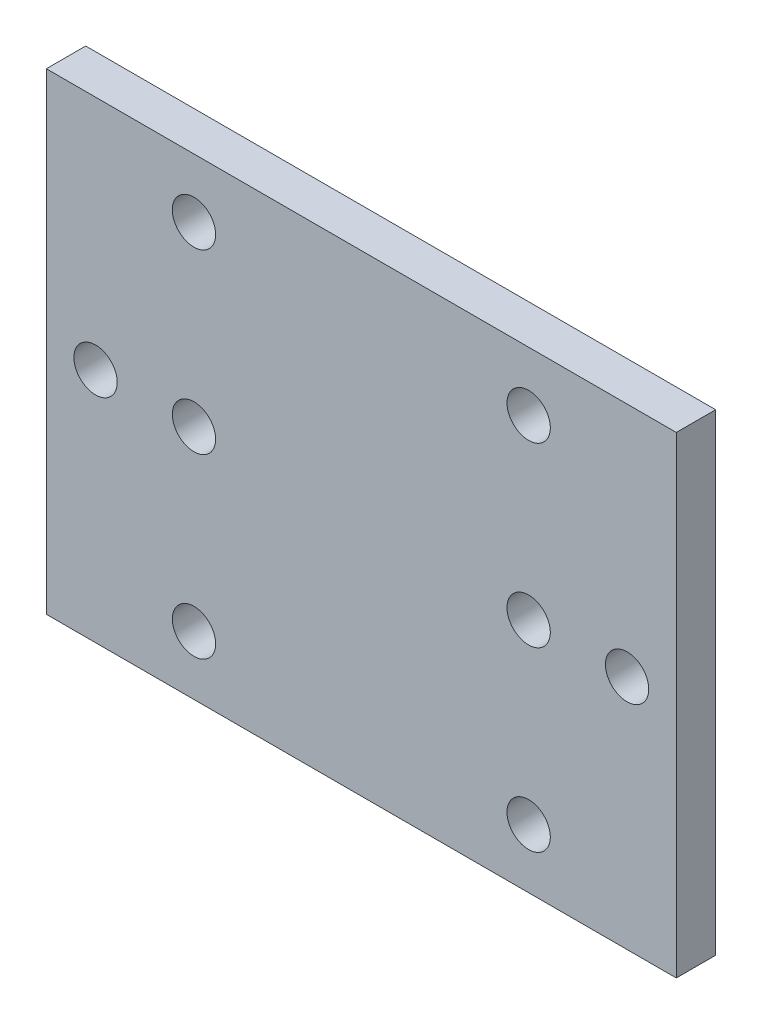
SolidWorks part; units mm, degrees
material "AISI 1015 Steel, Cold Drawn (SS)"
ref_plane "Front Plane" through (0, 0, 0) normal (0, 0, 1) x (1, 0, 0)
ref_plane "Top Plane" through (0, 0, 0) normal (0, 1, 0) x (1, 0, 0)
ref_plane "Right Plane" through (0, 0, 0) normal (1, 0, 0) x (0, 0, -1)
sketch "Sketch2" plane through (0, 0, 0) normal (0, 0, 1) x (1, 0, 0)
  line L1 (-101.6, -76.2) -> (101.6, -76.2)
  line L2 (-101.6, -76.2) -> (-101.6, 76.2)
  line L3 (-101.6, 76.2) -> (101.6, 76.2)
  line L4 (101.6, -76.2) -> (101.6, 76.2)
  line L5 (-101.6, -76.2) -> (101.6, 76.2) construction
  line L6 (-101.6, 76.2) -> (101.6, -76.2) construction
  point P0 (0, 0)
  dimension "D1" = 152.4
  dimension "D2" = 203.2
extrude "Boss-Extrude1" add sketch "Sketch2" along normal blind 12.7
sketch "Sketch3" plane through (0, 0, 0) normal (0, 0, -1) x (-1, 0, 0)
  line L0 (-101.6, 57.15) -> (-85.725, 57.15) construction
  line L2 (-53.975, 57.15) -> (-53.975, -57.15) construction
  line L3 (-53.975, -57.15) -> (-85.725, -57.15) construction
  line L4 (-85.725, 76.2) -> (-85.725, 57.15) construction
  line L6 (-101.6, -76.2) -> (-101.6, 76.2) construction
  line L7 (-85.725, 57.15) -> (-53.975, 57.15) construction
  line L8 (-101.6, 76.2) -> (101.6, 76.2) construction
  line L9 (-85.725, 57.15) -> (-85.725, -57.15) construction
  line L10 (-53.975, 57.15) -> (0, 57.15) construction
  line L11 (0, 57.15) -> (0, 250.2677) construction
  circle A0 centre (-85.725, 57.15) radius 6.985
  circle A1 centre (-53.975, 57.15) radius 6.985
  circle A2 centre (-53.975, -57.15) radius 6.985
  circle A3 centre (-85.725, -57.15) radius 6.985
  circle A4 centre (-85.725, 0) radius 6.985
  circle A5 centre (-53.975, 0) radius 6.985
  circle A6 centre (53.975, 57.15) radius 6.985
  circle A7 centre (85.725, 57.15) radius 6.985
  circle A8 centre (85.725, 0) radius 6.985
  circle A9 centre (85.725, -57.15) radius 6.985
  circle A10 centre (53.975, -57.15) radius 6.985
  circle A11 centre (53.975, 0) radius 6.985
  dimension "D5" = 13.97
  dimension "D1" = 15.875
  dimension "D2" = 114.3
  dimension "D3" = 31.75
  dimension "D4" = 19.05
  dimension "D6" = 101.6
extrude "Cut-Extrude1" cut sketch "Sketch3" against normal through all contours A11 | A8 | A10 | A5 | A6 | A2 | A4 | A1
mirror "Mirror1" [suppressed] about plane through (0, 0, 0) normal (1, 0, 0)
fillet "Fillet1" [suppressed] radius 1.27
